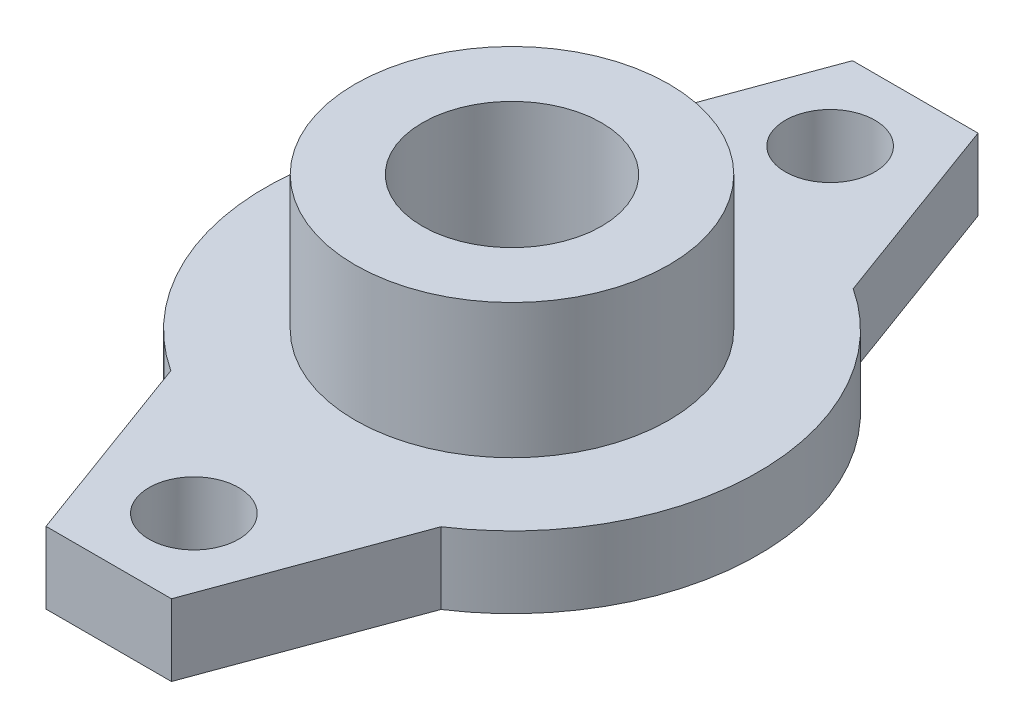
SolidWorks part; units mm, degrees
material "3.0205 (EN-AW 1200)"
ref_plane "Plan de face" through (0, 0, 0) normal (0, 0, 1) x (1, 0, 0)
ref_plane "Plan de dessus" through (0, 0, 0) normal (0, 1, 0) x (1, 0, 0)
ref_plane "Plan de droite" through (0, 0, 0) normal (1, 0, 0) x (0, 0, -1)
sketch "Esquisse1" plane through (0, 0, 0) normal (0, 1, 0) x (1, 0, 0)
  line L0 (-15.0748, 23) -> (-7, 45)
  line L1 (-7, 45) -> (7, 45)
  line L2 (0, 45) -> (0, -45) construction
  line L3 (0, 0) -> (-27.5, 0) construction
  line L4 (0, -55) -> (0, 55) construction
  line L5 (15.0748, 23) -> (7, 45)
  line L6 (-55, 0) -> (55, 0) construction
  line L7 (15.0748, -23) -> (7, -45)
  line L8 (-7, -45) -> (7, -45)
  line L9 (-15.0748, -23) -> (-7, -45)
  arc A0 (-15.0748, -23) -> (-15.0748, 23) centre (0, 0) cw
  arc A1 (15.0748, -23) -> (15.0748, 23) centre (0, 0) ccw
  point P5 (-27.5, 0)
  dimension "D1" = 27.5
  dimension "D2" = 45
  dimension "D3" = 7
  dimension "D4" = 23
extrude "Boss.-Extru.1" add sketch "Esquisse1" along normal blind 8
sketch "Esquisse2" plane through (0, 8, 0) normal (0, 1, 0) x (1, 0, 0)
  circle A0 centre (0, 0) radius 17.5
  circle A1 centre (0, 0) radius 10
  dimension "D1" = 35
  dimension "D2" = 20
extrude "Boss.-Extru.2" add sketch "Esquisse2" along normal blind 15
sketch "Esquisse3" plane through (0, 8, 0) normal (0, 1, 0) x (1, 0, 0)
  circle A0 centre (0, 0) radius 10 construction
  circle A1 centre (0, 0) radius 10
extrude "Enlèv. mat.-Extru.1" cut sketch "Esquisse3" against normal blind 10
sketch "Esquisse4" plane through (0, 8, 0) normal (0, 1, 0) x (1, 0, 0)
  circle A0 centre (0, 0) radius 35.5 construction
  circle A1 centre (0, 35.5) radius 5
  circle A2 centre (0, -35.5) radius 5
  dimension "D1" = 71
  dimension "D2" = 10
  dimension "D3" = 10
extrude "Enlèv. mat.-Extru.2" cut sketch "Esquisse4" against normal blind 10
